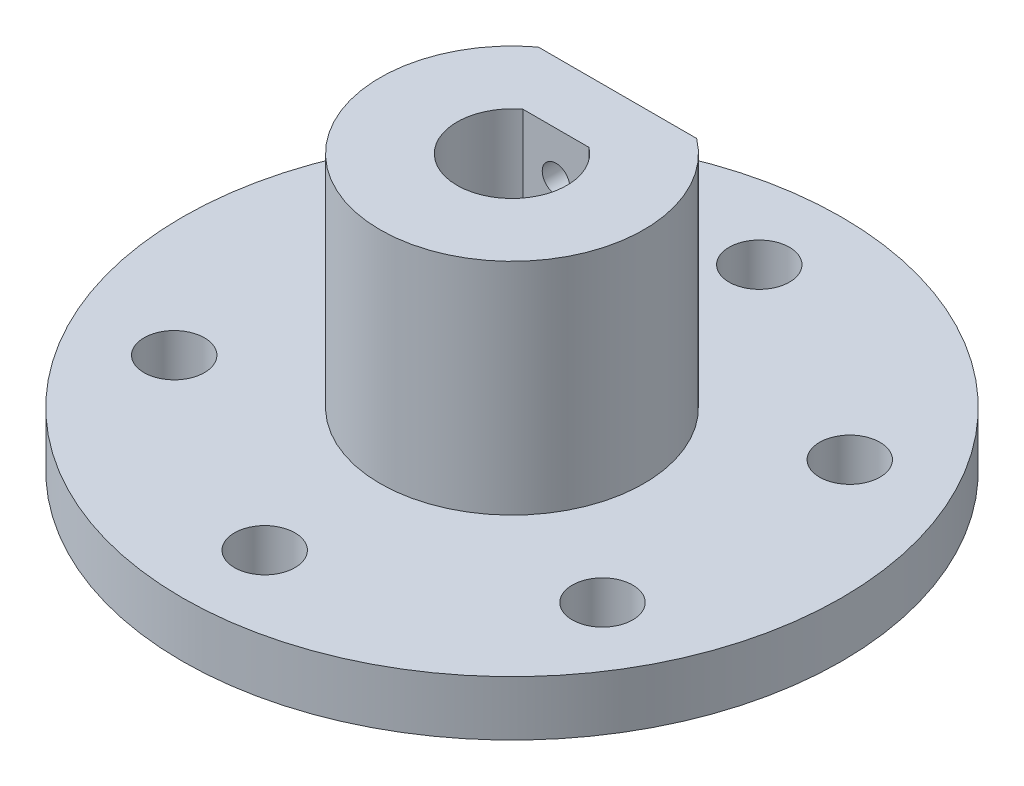
SolidWorks part; units mm, degrees
material "6061 合金"
ref_plane "前视基准面" through (0, 0, 0) normal (0, 0, 1) x (1, 0, 0)
ref_plane "上视基准面" through (0, 0, 0) normal (0, 1, 0) x (1, 0, 0)
ref_plane "右视基准面" through (0, 0, 0) normal (1, 0, 0) x (0, 0, -1)
sketch "草图1" plane through (0, 0, 0) normal (0, 1, 0) x (1, 0, 0)
  circle A0 centre (0, 0) radius 30
  circle A1 centre (0, 0) radius 22.5 construction
  circle A2 centre (0, 22.5) radius 2.75
  circle A3 centre (19.4856, 11.25) radius 2.75
  circle A4 centre (19.4856, -11.25) radius 2.75
  circle A5 centre (0, -22.5) radius 2.75
  circle A6 centre (-19.4856, -11.25) radius 2.75
  circle A7 centre (-19.4856, 11.25) radius 2.75
  circle A8 centre (0, 0) radius 2.51
  point P19 (0, 0)
  dimension "D1" = 60
  dimension "D2" = 45
  dimension "D3" = 5.5
  dimension "D5" = 5.02
  dimension "D4" = 6
extrude "凸台-拉伸1" add sketch "草图1" along normal blind 5
sketch "草图2" plane through (0, 5, 0) normal (0, 1, 0) x (1, 0, 0)
  line L0 (-7.2, 9.6) -> (7.2, 9.6)
  line L1 (3, 4) -> (-3, 4)
  arc A0 (-7.2, 9.6) -> (7.2, 9.6) centre (0, 0) ccw
  arc A1 (-3, 4) -> (3, 4) centre (0, 0) ccw
  dimension "D1" = 24
  dimension "D3" = 10
  dimension "D2" = 9.6
  dimension "D4" = 4
extrude "凸台-拉伸2" add sketch "草图2" along normal blind 20
hole_wizard "M3 螺纹孔1" positions "草图3" profile "草图4" tap size "M3" standard "GB"
sketch "草图3" plane through (0, 0, -9.6) normal (0, 0, -1) x (-1, 0, 0)
  line L0 (-7.2, 25) -> (7.2, 25) construction
  point P0 (0, 21)
  dimension "D1" = 4
sketch "草图4" plane through (0, 21, -9.6) normal (1, 0, 0) x (0, 1, 0)
  line L0 (0, 0) -> (0, 5.6)
  line L1 (0, 5.6) -> (1.25, 5.6)
  line L2 (1.25, 5.6) -> (1.25, 0)
  line L5 (1.25, 0) -> (0, 0)
  line L11 (0, -6.35) -> (0, 107.95) construction
  dimension "通孔螺纹孔钻头直径" = 2.5
  dimension "通孔螺纹孔钻头深度" = 5.6
cosmetic thread "孔螺蚊线1" parameters "D2"=3
sketch "草图5" plane through (0, 0, -9.6) normal (0, 0, -1) x (-1, 0, 0)
  line L0 (30, 5) -> (-30, 5) construction
  circle A0 centre (0, 15) radius 1.6
  dimension "D1" = 3.2
  dimension "D2" = 10
extrude "切除-拉伸1" cut sketch "草图5" against normal up to next
